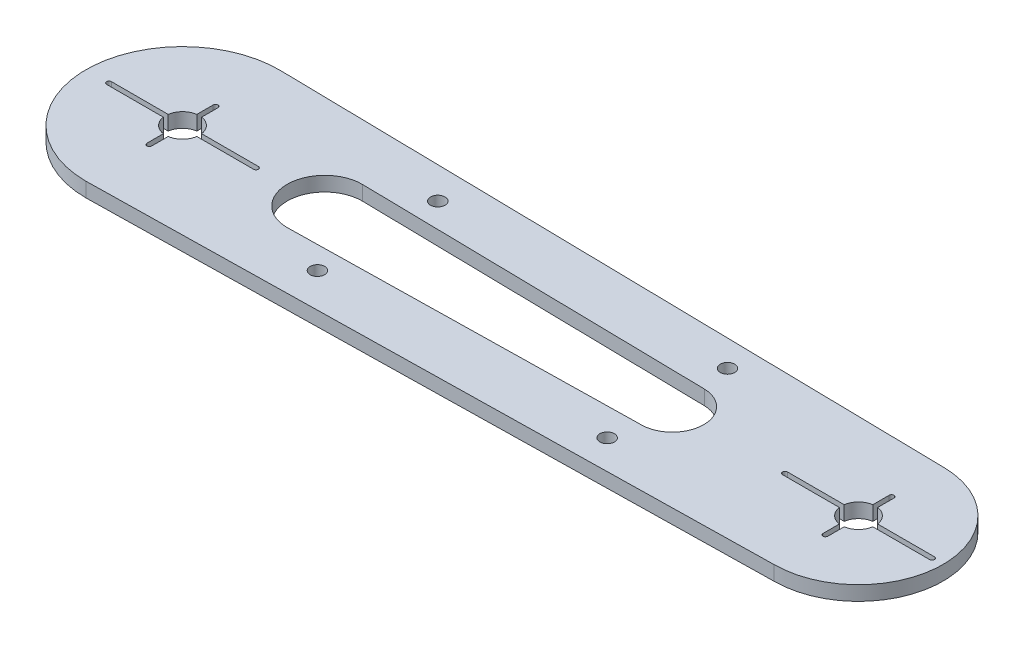
SolidWorks part; units mm, degrees
ref_plane "Front Plane" through (0, 0, 0) normal (0, 0, 1) x (1, 0, 0)
ref_plane "Top Plane" through (0, 0, 0) normal (0, 1, 0) x (1, 0, 0)
ref_plane "Right Plane" through (0, 0, 0) normal (1, 0, 0) x (0, 0, -1)
sketch "Sketch1" plane through (0, 0, 0) normal (0, 1, 0) x (1, 0, 0)
  line L0 (0.3571, 19.9968) -> (140.3125, 17.4972)
  line L1 (140, -17.5) -> (0, -20)
  circle A0 centre (0, 0) radius 20
  circle A1 centre (140, 0) radius 17.5
  point P11 (70.9941, 1.1797)
  dimension "D1" = 140
  dimension "D2" = 40
  dimension "D3" = 35
extrude "Boss-Extrude1" add sketch "Sketch1" along normal blind 3 contours L1 A0 | A1 L0 A0 L1 | A1 A0
sketch "Sketch2" plane through (0, 3, 0) normal (0, 1, 0) x (1, 0, 0)
  circle A0 centre (0, 0) radius 3.4
  circle A1 centre (140, 0) radius 3.375
  dimension "D1" = 6.8
  dimension "D2" = 6.75
extrude "Cut-Extrude1" cut sketch "Sketch2" against normal through all
sketch "Sketch4" plane through (0, 3, 0) normal (0, 1, 0) x (1, 0, 0)
  line L0 (101.2839, 6.7707) -> (29.173, 8.0586)
  line L1 (29.1576, -7.4774) -> (101.4946, -6.1857)
  arc A6 (29.173, 8.0586) -> (29.1576, -7.4774) centre (29.1653, 0.2906) ccw
  arc A7 (101.2839, 6.7707) -> (101.0524, -6.1936) centre (101.1578, 0.2888) cw
  dimension "D2" = 7.768
  dimension "D3" = 6.4832
  dimension "D1" = 72.337
  dimension "D4" = 2.046
extrude "Cut-Extrude3" cut sketch "Sketch4" against normal through all contours A7 L0 A6 L1
sketch "Sketch5" plane through (0, 3, 0) normal (0, 1, 0) x (1, 0, 0)
  line L0 (0, 0) -> (140, 0) construction
  line L1 (70, 31.2057) -> (70, -26.0603) construction
  circle A1 centre (0, 6.9681) radius 0.5
  circle A2 centre (-9.27, 0.0472) radius 0.5
  circle A3 centre (0, -7.7251) radius 0.5
  circle A4 centre (9.9339, 0) radius 0.5
  dimension "D3" = 1
  dimension "D4" = 9.27
  dimension "D1" = 140
  dimension "D2" = 70
sketch "Sketch6" plane through (0, 0, 0) normal (0, 1, 0) x (1, 0, 0)
  line L0 (-15.22, 0) -> (15.22, 0) construction
  line L1 (0, 0) -> (140, 0) construction
  line L2 (-15.22, 0.5) -> (15.22, 0.5)
  line L3 (-15.22, -0.5) -> (15.22, -0.5)
  line L4 (0, -6.855) -> (0, 6.855) construction
  line L5 (-0.5, -6.855) -> (-0.5, 6.855)
  line L6 (0.5, -6.855) -> (0.5, 6.855)
  arc A0 (-15.22, 0.5) -> (-15.22, -0.5) centre (-15.22, 0) ccw
  arc A1 (15.22, -0.5) -> (15.22, 0.5) centre (15.22, 0) ccw
  arc A2 (-0.5, -6.855) -> (0.5, -6.855) centre (0, -6.855) ccw
  arc A3 (0.5, 6.855) -> (-0.5, 6.855) centre (0, 6.855) ccw
  point P5 (0, 0)
  point P11 (0, 0)
  dimension "D1" = 0.5
  dimension "D2" = 0.5
  dimension "D3" = 30.44
  dimension "D4" = 13.71
extrude "Cut-Extrude4" cut sketch "Sketch6" along normal through all contours L2 A0 L3 L5 | L6 A3 L5 L2 | L5 A2 L6 L3
sketch "Sketch7" plane through (0, 3, 0) normal (0, 1, 0) x (1, 0, 0)
  line L0 (155.22, 0) -> (124.78, 0) construction
  line L1 (0, 0) -> (140, 0) construction
  line L2 (155.22, -0.5) -> (124.78, -0.5)
  line L3 (155.22, 0.5) -> (124.78, 0.5)
  line L4 (140, -6.855) -> (140, 6.855) construction
  line L5 (139.5, -6.855) -> (139.5, 6.855)
  line L6 (140.5, -6.855) -> (140.5, 6.855)
  arc A0 (155.22, -0.5) -> (155.22, 0.5) centre (155.22, 0) ccw
  arc A1 (124.78, 0.5) -> (124.78, -0.5) centre (124.78, 0) ccw
  arc A2 (139.5, -6.855) -> (140.5, -6.855) centre (140, -6.855) ccw
  arc A3 (140.5, 6.855) -> (139.5, 6.855) centre (140, 6.855) ccw
  point P5 (140, 0)
  point P11 (140, 0)
  circle M3 centre (140, 0) radius 3.375
  dimension "D1" = 0.5
  dimension "D2" = 0.5
  dimension "D3" = 30.44
  dimension "D4" = 13.71
extrude "Cut-Extrude5" cut sketch "Sketch7" against normal through all contours L6 A3 L5 M3 | L3 A1 L2 A0
sketch "Sketch8" plane through (0, 3, 0) normal (0, 1, 0) x (1, 0, 0)
  circle A0 centre (0, 0) radius 3.5
  circle A1 centre (140, 0) radius 3.5
  dimension "D1" = 7
  dimension "D2" = 7
extrude "Cut-Extrude6" cut sketch "Sketch8" against normal through all
sketch "Sketch10" plane through (0, 3, 0) normal (0, 1, 0) x (1, 0, 0)
  line L0 (70, 7.5111) -> (70, -7.999) construction
  line L1 (70, 31.2057) -> (70, -26.0603) construction
  line L2 (101.2839, 6.7707) -> (29.173, 8.0586) construction
  circle A0 centre (40, 12.8661) radius 1.5
  circle A1 centre (40, -12.0554) radius 1.5
  circle A2 centre (100, -12.0554) radius 1.5
  circle A3 centre (100, 12.8661) radius 1.5
  dimension "D1" = 3
  dimension "D2" = 3
  dimension "D4" = 5
  dimension "D3" = 30
extrude "Cut-Extrude7" cut sketch "Sketch10" against normal blind 10
